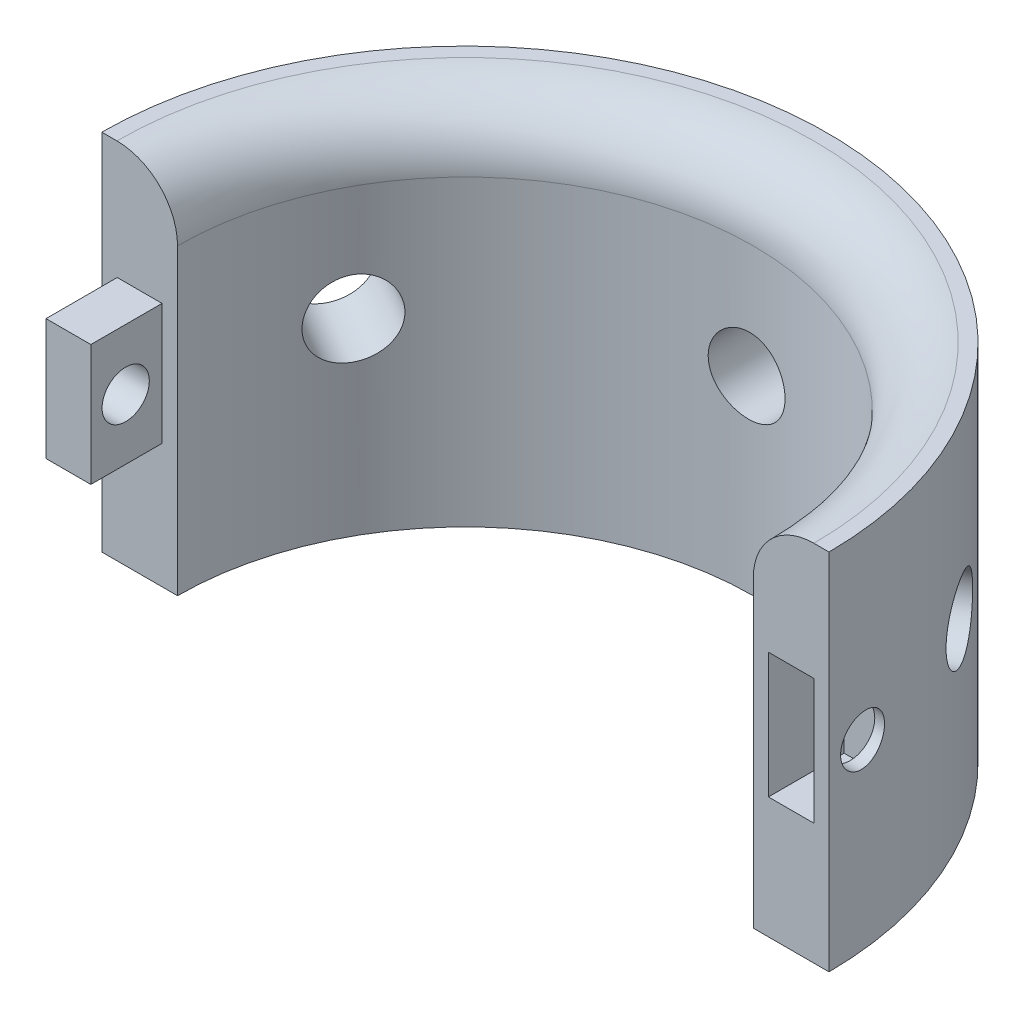
SolidWorks part; units mm, degrees
ref_plane "Front Plane" through (0, 0, 0) normal (0, 0, 1) x (1, 0, 0)
ref_plane "Top Plane" through (0, 0, 0) normal (0, 1, 0) x (1, 0, 0)
ref_plane "Right Plane" through (0, 0, 0) normal (1, 0, 0) x (0, 0, -1)
sketch "Sketch1" plane through (0, 0, 0) normal (0, 1, 0) x (1, 0, 0)
  line L1 (-78.9587, 0) -> (-17.9987, 0)
  arc A0 (-78.9587, 0) -> (-17.9987, 0) centre (-48.4787, -0.1303) cw
  dimension "D1" = 60.96
extrude "Boss-Extrude1" add sketch "Sketch1" along normal blind 30.48 contours L1 A0
ref_plane "Plane1" through (-17.9987, 30.48, 0) normal (1, 0, 0) x (0, 0, -1)
sketch "Sketch3" plane through (0, 0, 0) normal (0, 1, 0) x (1, 0, 0)
  line L0 (-78.9587, 0) -> (-17.9987, 0) construction
  circle A0 centre (-48.4787, 0) radius 24.13
  dimension "D1" = 48.26
extrude "Cut-Extrude4" cut sketch "Sketch3" along normal through all contours A0
sketch "Sketch4" plane through (0, 0, 0) normal (0, 0, 1) x (1, 0, 0)
  circle A0 centre (-48.8244, 15.7989) radius 3.175
  point P2 (0, 0)
  dimension "D1" = 6.35
extrude "Cut-Extrude5" cut sketch "Sketch4" against normal blind 63.754 contours A0
pattern_circular "CirPattern3" count 6 every 60 about axis through (-48.4787, 30.48, 0.1303) along (0, -1, 0) of "Cut-Extrude5"
sketch "Sketch6" plane through (0, 0, 0) normal (0, 0, 1) x (1, 0, 0)
  line L0 (-24.3487, 0) -> (-17.9987, 0) construction
  line L1 (-19.2687, 10.16) -> (-23.0787, 10.16)
  line L2 (-19.2687, 10.16) -> (-19.2687, 20.6694)
  line L3 (-19.2687, 20.6694) -> (-23.0787, 20.6694)
  line L4 (-23.0787, 10.16) -> (-23.0787, 20.6694)
  line L5 (-17.9987, 30.48) -> (-17.9987, 0) construction
  line L6 (-24.3487, 0) -> (-24.3487, 30.48) construction
  point P6 (-21.1737, 0)
  point P11 (-24.3487, 15.24)
  dimension "D1" = 10.16
  dimension "D2" = 1.27
  dimension "D3" = 1.27
extrude "Cut-Extrude6" cut sketch "Sketch6" against normal blind 6.35
sketch "Sketch7" plane through (0, 0, 0) normal (0, 0, 1) x (1, 0, 0)
  line L0 (-78.9587, 0) -> (-72.6087, 0) construction
  line L1 (-77.6633, 20.574) -> (-73.9041, 20.574)
  line L2 (-77.6633, 20.574) -> (-77.6633, 10.414)
  line L3 (-77.6633, 10.414) -> (-73.9041, 10.414)
  line L4 (-73.9041, 20.574) -> (-73.9041, 10.414)
  line L5 (-78.9587, 30.48) -> (-78.9587, 0) construction
  line L6 (-72.6087, 30.48) -> (-72.6087, 0) construction
  line L8 (-19.2687, 20.6694) -> (-23.0787, 20.6694) construction
  dimension "D1" = 10.414
  dimension "D2" = 1.2954
  dimension "D3" = 1.2954
  dimension "D4" = 10.16
extrude "Boss-Extrude4" add sketch "Sketch7" along normal blind 5.969
sketch "Sketch8" plane through (-73.9041, 0, 0) normal (1, 0, 0) x (0, 0, -1)
  line L0 (-5.969, 10.414) -> (0, 10.414) construction
  line L1 (0, 10.414) -> (0, 20.574) construction
  circle A0 centre (-3.048, 15.494) radius 1.9808
  dimension "D1" = 5.08
  dimension "D2" = 3.048
extrude "Cut-Extrude7" cut sketch "Sketch8" against normal blind 5.969
sketch "Sketch9" plane through (-23.0787, 0, 0) normal (1, 0, 0) x (0, 0, -1)
  line L0 (0, 20.6694) -> (0, 10.16) construction
  line L1 (6.35, 10.16) -> (0, 10.16) construction
  circle A0 centre (3.048, 15.24) radius 2.0568
  dimension "D1" = 3.048
  dimension "D2" = 5.08
extrude "Cut-Extrude8" cut sketch "Sketch9" along normal blind 12.319
fillet "Fillet4" radius 5.08 1 edges at (-48.4787, 30.48, -24.13)
